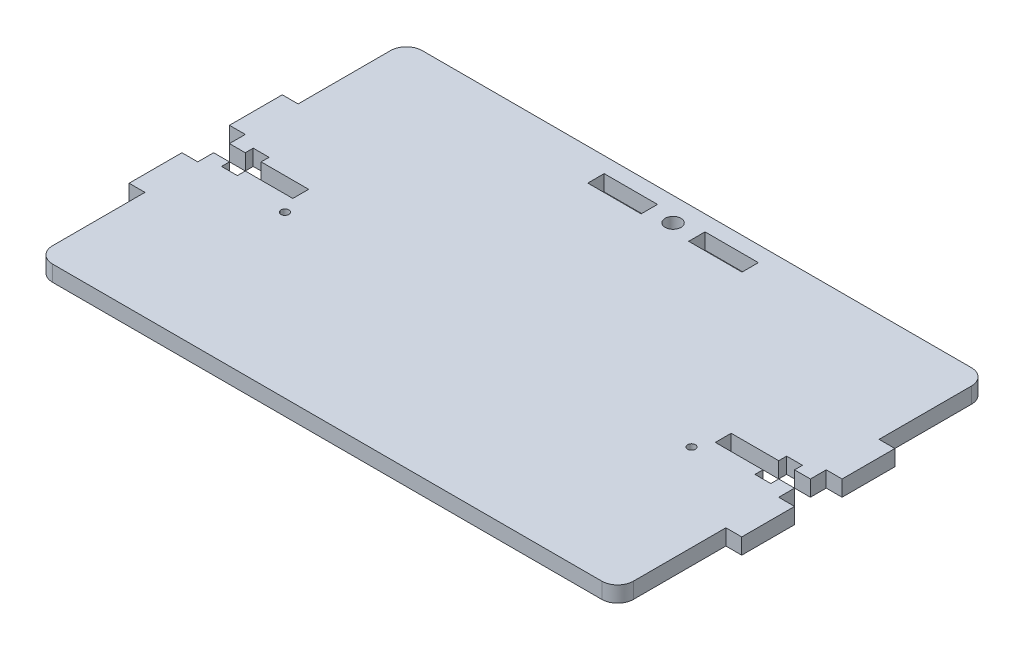
SolidWorks part; units mm, degrees
ref_plane "Front Plane" through (0, 0, 0) normal (0, 0, 1) x (1, 0, 0)
ref_plane "Top Plane" through (0, 0, 0) normal (0, 1, 0) x (1, 0, 0)
ref_plane "Right Plane" through (0, 0, 0) normal (1, 0, 0) x (0, 0, -1)
sketch "Sketch1" plane through (0, 0, 0) normal (0, 1, 0) x (1, 0, 0)
  line L0 (55, 70) -> (55, 0) construction
  line L1 (0, 0) -> (110, 0)
  line L2 (0, 0) -> (0, 70)
  line L3 (0, 70) -> (110, 70)
  line L4 (110, 0) -> (110, 70)
  line L5 (0, 35) -> (110, 35) construction
  line L6 (107, 38) -> (107, 32)
  line L7 (0, 36.5) -> (15, 36.5)
  line L8 (0, 36.5) -> (0, 33.5)
  line L9 (0, 33.5) -> (15, 33.5)
  line L10 (15, 36.5) -> (15, 33.5)
  line L11 (3, 38) -> (6, 38)
  line L12 (3, 38) -> (3, 32)
  line L13 (3, 32) -> (6, 32)
  line L14 (6, 38) -> (6, 32)
  line L15 (107, 32) -> (104, 32)
  line L16 (104, 38) -> (104, 32)
  line L17 (107, 38) -> (104, 38)
  line L18 (110, 36.5) -> (110, 33.5)
  line L19 (110, 33.5) -> (95, 33.5)
  line L20 (95, 36.5) -> (95, 33.5)
  line L21 (110, 36.5) -> (95, 36.5)
  line L22 (0, 30.5) -> (0, 20.5)
  line L23 (0, 39.5) -> (-3, 39.5)
  line L24 (0, 39.5) -> (0, 49.5)
  line L25 (0, 49.5) -> (-3, 49.5)
  line L26 (-3, 39.5) -> (-3, 49.5)
  line L27 (0, 30.5) -> (-3, 30.5)
  line L28 (-3, 30.5) -> (-3, 20.5)
  line L29 (0, 20.5) -> (-3, 20.5)
  line L30 (110, 30.5) -> (110, 20.5)
  line L31 (110, 20.5) -> (113, 20.5)
  line L32 (113, 30.5) -> (113, 20.5)
  line L33 (110, 30.5) -> (113, 30.5)
  line L34 (110, 39.5) -> (110, 49.5)
  line L35 (110, 39.5) -> (113, 39.5)
  line L36 (113, 39.5) -> (113, 49.5)
  line L37 (110, 49.5) -> (113, 49.5)
  line L38 (0, 65.5) -> (110, 65.5) construction
  line L39 (69.6, 67.05) -> (59.5, 67.05)
  line L40 (40.4, 67.05) -> (50.5, 67.05)
  line L41 (40.4, 67.05) -> (40.4, 63.95)
  line L42 (40.4, 63.95) -> (50.5, 63.95)
  line L43 (50.5, 67.05) -> (50.5, 63.95)
  line L44 (69.6, 67.05) -> (69.6, 63.95)
  line L45 (69.6, 63.95) -> (59.5, 63.95)
  line L46 (59.5, 67.05) -> (59.5, 63.95)
  circle A0 centre (16.5, 30.5) radius 0.75
  circle A1 centre (93.5, 30.5) radius 0.75
  circle A2 centre (55, 65.5) radius 1.5
  point P13 (0, 35)
  point P18 (3, 35)
  point P55 (50.5, 65.5)
  dimension "D11" = 1.5
  dimension "D15" = 3
  dimension "D1" = 70
  dimension "D2" = 110
  dimension "D3" = 3
  dimension "D4" = 3
  dimension "D5" = 6
  dimension "D6" = 3
  dimension "D7" = 15
  dimension "D8" = 10
  dimension "D9" = 4.5
  dimension "D10" = 3
  dimension "D12" = 38.5
  dimension "D13" = 4.5
  dimension "D14" = 4.5
  dimension "D16" = 10.1
  dimension "D17" = 3.1
  dimension "D18" = 4.5
extrude "Boss-Extrude1" add sketch "Sketch1" along normal blind 3 contours L21 L4 L3 L2 L7 L12 L11 L14 L10 L9 L13 L1 L19 L6 L15 L16 L20 L17 | L29 L2 L27 L28 | L26 L23 L2 L25 | L33 L4 L31 L32 | L37 L4 L35 L36
fillet "Fillet1" radius 3 4 edges at (110, 1.5, 0) (110, 1.5, -70) (0, 1.5, 0) (0, 1.5, -70)
equation "\"D12@Sketch1\"=77/2"
